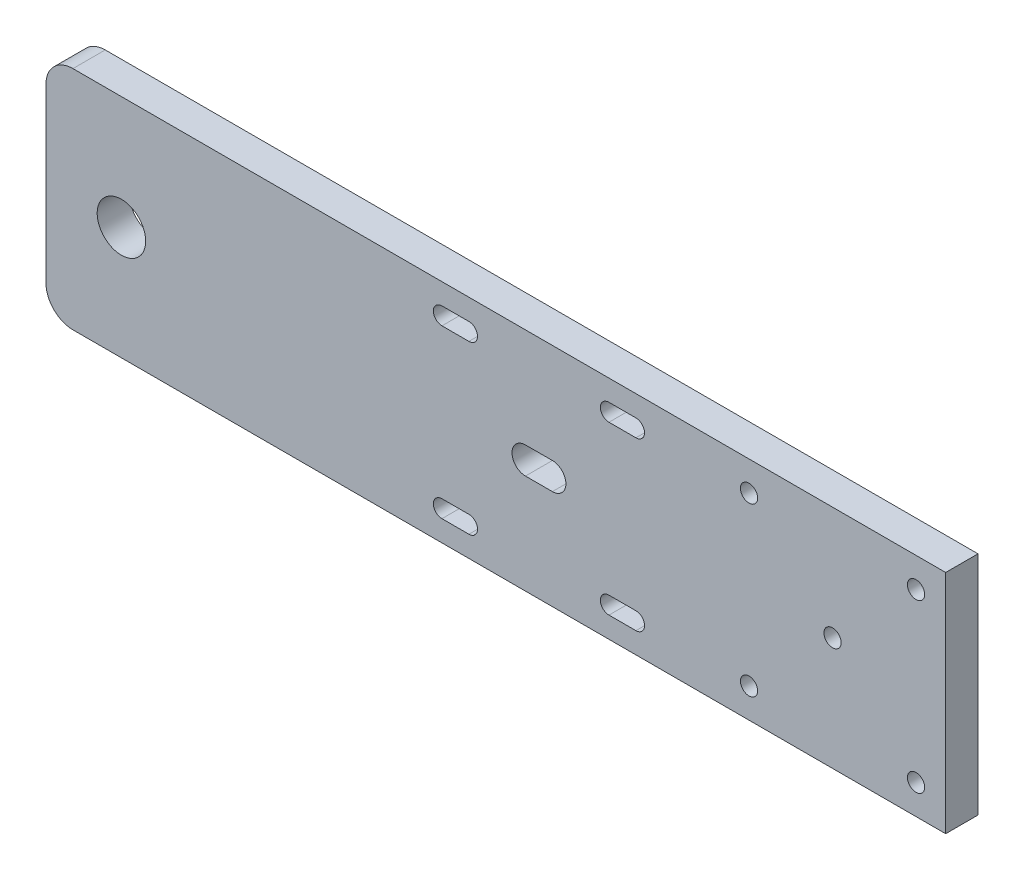
SolidWorks part; units mm, degrees
ref_plane "前视基准面" through (0, 0, 0) normal (0, 0, 1) x (1, 0, 0)
ref_plane "上视基准面" through (0, 0, 0) normal (0, 1, 0) x (1, 0, 0)
ref_plane "右视基准面" through (0, 0, 0) normal (1, 0, 0) x (0, 0, -1)
sketch "草图1" plane through (0, 0, 0) normal (0, 0, 1) x (1, 0, 0)
  line L0 (-78, 21) -> (-36, 21)
  line L1 (-21, 21) -> (21, 21)
  line L2 (-21, 21) -> (-21, -21)
  line L3 (-21, -21) -> (21, -21)
  line L4 (21, 21) -> (21, -21)
  line L5 (-21, 21) -> (21, -21) construction
  line L6 (-21, -21) -> (21, 21) construction
  line L9 (21, -21) -> (20.1154, -21)
  line L11 (-21, 21) -> (-141, 21)
  line L12 (-21, 21) -> (-21, -21)
  line L13 (-21, -21) -> (-141, -21)
  line L14 (-141, 21) -> (-141, -21)
  line L19 (-73, 21) -> (-31, 21)
  line L20 (-73, 21) -> (-73, -21)
  line L21 (-73, -21) -> (-31, -21)
  line L22 (-31, 21) -> (-31, -21)
  line L23 (-73, 21) -> (-31, -21) construction
  line L24 (-73, -21) -> (-31, 21) construction
  line L25 (-78, 21) -> (-78, -21)
  line L26 (-78, -21) -> (-36, -21)
  line L27 (-36, 21) -> (-36, -21)
  line L28 (-78, 21) -> (-36, -21) construction
  line L29 (-78, -21) -> (-36, 21) construction
  line L30 (-72.5, 15.5) -> (-67.5, 15.5) construction
  line L31 (-72.5, 17.1) -> (-67.5, 17.1)
  line L32 (-72.5, 13.9) -> (-67.5, 13.9)
  line L33 (-41.5, 15.5) -> (-36.5, 15.5) construction
  line L34 (-41.5, 17.1) -> (-36.5, 17.1)
  line L35 (-41.5, 13.9) -> (-36.5, 13.9)
  line L36 (-72.5, -15.5) -> (-67.5, -15.5) construction
  line L37 (-72.5, -13.9) -> (-67.5, -13.9)
  line L38 (-72.5, -17.1) -> (-67.5, -17.1)
  line L39 (-41.5, -15.5) -> (-36.5, -15.5) construction
  line L40 (-41.5, -13.9) -> (-36.5, -13.9)
  line L41 (-41.5, -17.1) -> (-36.5, -17.1)
  line L42 (-57, 0) -> (-52, 0) construction
  line L43 (-57, 2.5) -> (-52, 2.5)
  line L44 (-57, -2.5) -> (-52, -2.5)
  line L46 (-141, 21) -> (-146, 21)
  line L47 (-141, 21) -> (-141, -21)
  line L48 (-141, -21) -> (-146, -21)
  line L49 (-146, 21) -> (-146, -21)
  circle A0 centre (0, 0) radius 1.6
  circle A1 centre (-15.5, 15.5) radius 1.6
  circle A2 centre (15.5, 15.5) radius 1.6
  circle A3 centre (-15.5, -15.5) radius 1.6
  circle A4 centre (15.5, -15.5) radius 1.6
  circle A9 centre (-132, 0) radius 4.5
  arc A14 (-72.5, 17.1) -> (-72.5, 13.9) centre (-72.5, 15.5) ccw
  arc A15 (-67.5, 13.9) -> (-67.5, 17.1) centre (-67.5, 15.5) ccw
  arc A16 (-41.5, 17.1) -> (-41.5, 13.9) centre (-41.5, 15.5) ccw
  arc A17 (-36.5, 13.9) -> (-36.5, 17.1) centre (-36.5, 15.5) ccw
  arc A18 (-72.5, -13.9) -> (-72.5, -17.1) centre (-72.5, -15.5) ccw
  arc A19 (-67.5, -17.1) -> (-67.5, -13.9) centre (-67.5, -15.5) ccw
  arc A20 (-41.5, -13.9) -> (-41.5, -17.1) centre (-41.5, -15.5) ccw
  arc A21 (-36.5, -17.1) -> (-36.5, -13.9) centre (-36.5, -15.5) ccw
  arc A22 (-57, 2.5) -> (-57, -2.5) centre (-57, 0) ccw
  arc A23 (-52, -2.5) -> (-52, 2.5) centre (-52, 0) ccw
  point P0 (0, 0)
  point P20 (-52, 0)
  point P26 (-54.5, 0)
  point P28 (-72.5, 15.5)
  point P31 (-70, -15.5)
  point P33 (-70, 15.5)
  point P43 (-67.5, 15.5)
  point P47 (-39, -15.5)
  point P48 (-57, 0)
  point P53 (-39, 15.5)
  point P58 (-41.5, 15.5)
  point P59 (-36.5, 15.5)
  dimension "D3" = 3.2
  dimension "D11" = 3.2
  dimension "D14" = 9
  dimension "D1" = 42
  dimension "D2" = 42
  dimension "D4" = 31
  dimension "D5" = 5
  dimension "D6" = 120
  dimension "D7" = 5
  dimension "D8" = 42
  dimension "D9" = 10
  dimension "D10" = 31
  dimension "D12" = 80
  dimension "D13" = 75
extrude "凸台-拉伸1" add sketch "草图1" along normal blind 6 contours L25 L11 L14 L13 A9 | A18 L20 A14 L0 L25 L13 | A21 L27 A17 L35 A16 L34 L11 L20 A14 L31 A15 L32 A18 L37 A19 L38 L21 L41 A20 L40 A23 L44 A22 L43 | A21 L27 L13 L22 L11 A17 | L11 L22 L13 L2 | L4 L1 L2 L3 A4 A3 A2 A1 A0 | L47 L46 L49 L48
fillet "圆角1" radius 5 2 edges at (-146, -21, 3) (-146, 21, 3)
